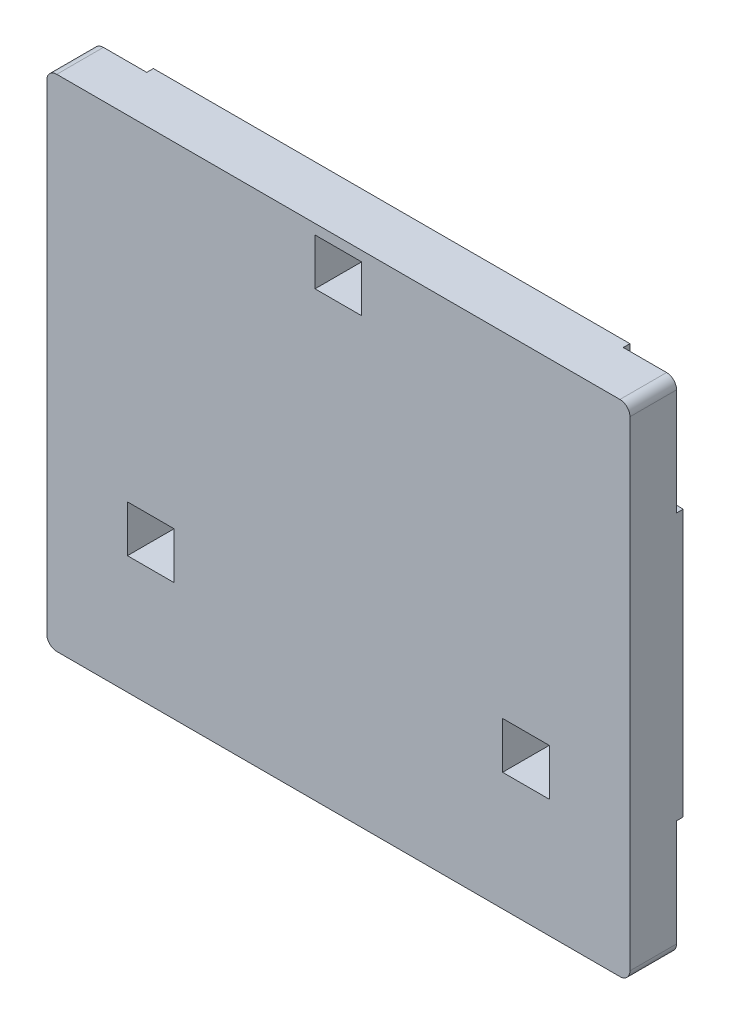
SolidWorks part; units mm, degrees
ref_plane "Front Plane" through (0, 0, 0) normal (0, 0, 1) x (1, 0, 0)
ref_plane "Top Plane" through (0, 0, 0) normal (0, 1, 0) x (1, 0, 0)
ref_plane "Right Plane" through (0, 0, 0) normal (1, 0, 0) x (0, 0, -1)
sketch "Sketch1" plane through (0, 0, 0) normal (0, 0, 1) x (1, 0, 0)
  line L1 (0, 0) -> (-175, 0)
  line L2 (0, 0) -> (0, -150)
  line L3 (0, -150) -> (-175, -150)
  line L4 (-175, 0) -> (-175, -150)
  dimension "D1" = 175
  dimension "D2" = 150
extrude "Boss-Extrude1" add sketch "Sketch1" along normal blind 16
sketch "Sketch2" plane through (0, 0, 16) normal (0, 0, 1) x (1, 0, 0)
  line L0 (-87.5, 0) -> (-87.5, -150) construction
  line L1 (0, 0) -> (-175, 0) construction
  line L2 (-175, -150) -> (0, -150) construction
  line L3 (-175, -75) -> (0, -75) construction
  line L4 (-87.5, -10) -> (-143.7917, -107.5) construction
  line L5 (0, -150) -> (0, 0) construction
  line L6 (-175, 0) -> (-175, -150) construction
  line L7 (-87.5, -10) -> (-31.2083, -107.5) construction
  line L8 (-143.7917, -107.5) -> (-31.2083, -107.5) construction
  line L10 (-80.5, -3) -> (-94.5, -3)
  line L11 (-80.5, -3) -> (-80.5, -17)
  line L12 (-80.5, -17) -> (-94.5, -17)
  line L13 (-94.5, -3) -> (-94.5, -17)
  line L14 (-80.5, -3) -> (-94.5, -17) construction
  line L15 (-80.5, -17) -> (-94.5, -3) construction
  line L16 (-136.7917, -114.5) -> (-150.7917, -114.5)
  line L17 (-136.7917, -114.5) -> (-136.7917, -100.5)
  line L18 (-136.7917, -100.5) -> (-150.7917, -100.5)
  line L19 (-150.7917, -114.5) -> (-150.7917, -100.5)
  line L20 (-136.7917, -114.5) -> (-150.7917, -100.5) construction
  line L21 (-136.7917, -100.5) -> (-150.7917, -114.5) construction
  line L22 (-24.2083, -114.5) -> (-38.2083, -114.5)
  line L23 (-24.2083, -114.5) -> (-24.2083, -100.5)
  line L24 (-24.2083, -100.5) -> (-38.2083, -100.5)
  line L25 (-38.2083, -114.5) -> (-38.2083, -100.5)
  line L26 (-24.2083, -114.5) -> (-38.2083, -100.5) construction
  line L27 (-24.2083, -100.5) -> (-38.2083, -114.5) construction
  circle A0 centre (-143.7917, -107.5) radius 7.5 construction
  circle A1 centre (-87.5, -10) radius 7.5 construction
  circle A2 centre (-31.2083, -107.5) radius 7.5 construction
  circle A4 centre (-87.5, -75) radius 65 construction
  dimension "D1" = 15
  dimension "D2" = 130
  dimension "D3" = 14
  dimension "D4" = 14
  dimension "D5" = 14
  dimension "D6" = 14
  dimension "D7" = 14
  dimension "D8" = 14
extrude "Cut-Extrude1" cut sketch "Sketch2" against normal blind 14
sketch "Sketch4" plane through (0, 0, 0) normal (0, 0, -1) x (-1, 0, 0)
  line L1 (175, 0) -> (159, 0)
  line L2 (175, 0) -> (175, -35)
  line L3 (175, -35) -> (159, -35)
  line L4 (159, 0) -> (159, -35)
  line L5 (175, -150) -> (159, -150)
  line L6 (175, -150) -> (175, -115)
  line L7 (175, -115) -> (159, -115)
  line L8 (159, -150) -> (159, -115)
  line L9 (0, -150) -> (16, -150)
  line L10 (0, -150) -> (0, -115)
  line L11 (0, -115) -> (16, -115)
  line L12 (16, -150) -> (16, -115)
  line L13 (0, 0) -> (16, 0)
  line L14 (0, 0) -> (0, -35)
  line L15 (0, -35) -> (16, -35)
  line L16 (16, 0) -> (16, -35)
  dimension "D1" = 35
  dimension "D2" = 16
extrude "Cut-Extrude5" cut sketch "Sketch4" against normal blind 2
fillet "Fillet1" radius 3 4 edges at (0, 0, 9) (0, -150, 9) (-175, -150, 9) (-175, 0, 9)
